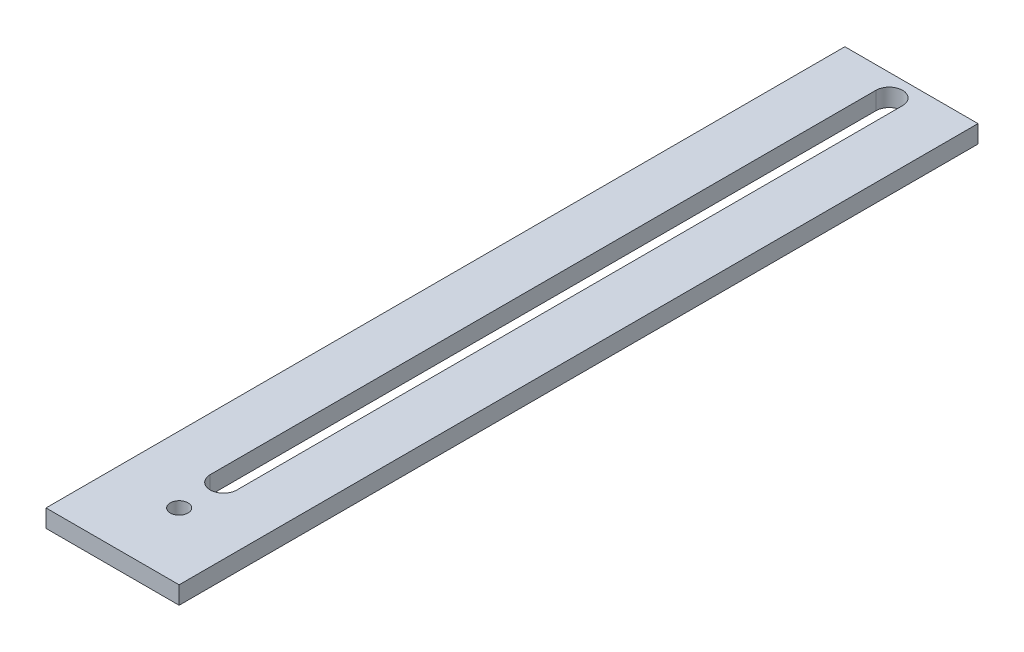
SolidWorks part; units mm, degrees
ref_plane "Front Plane" through (0, 0, 0) normal (0, 0, 1) x (1, 0, 0)
ref_plane "Top Plane" through (0, 0, 0) normal (0, 1, 0) x (1, 0, 0)
ref_plane "Right Plane" through (0, 0, 0) normal (1, 0, 0) x (0, 0, -1)
sketch "Sketch1" plane through (0, 0, 0) normal (0, 1, 0) x (1, 0, 0)
  line L1 (-15, 15) -> (15, 15)
  line L2 (-15, 15) -> (-15, -15)
  line L3 (-15, -15) -> (15, -15)
  line L4 (15, 15) -> (15, -15)
  line L5 (-15, 15) -> (15, -15) construction
  line L6 (-15, -15) -> (15, 15) construction
  circle A0 centre (0, 0) radius 2
  point P0 (0, 0)
  dimension "D1" = 4
  dimension "D2" = 30
  dimension "D3" = 30
extrude "Boss-Extrude1" add sketch "Sketch1" along normal blind 4
sketch "Sketch2" plane through (0, 0, -15) normal (0, 0, -1) x (-1, 0, 0)
  line L4 (-15, 0) -> (15, 0)
  line L5 (15, 0) -> (15, 4)
  line L6 (15, 4) -> (-15, 4)
  line L7 (-15, 4) -> (-15, 0)
  line L8 (-15, 0) -> (15, 0)
  line L9 (15, 0) -> (15, 4)
  line L10 (15, 4) -> (-15, 4)
  line L11 (-15, 4) -> (-15, 0)
  dimension "D1" = 0
extrude "Boss-Extrude2" add sketch "Sketch2" along normal blind 150
sketch "Sketch3" plane through (0, 4, 0) normal (0, 1, 0) x (1, 0, 0)
  line L0 (0, 10) -> (0, 160) construction
  line L1 (-3, 10) -> (-3, 160)
  line L2 (3, 10) -> (3, 160)
  arc A0 (-3, 10) -> (3, 10) centre (0, 10) ccw
  arc A1 (3, 160) -> (-3, 160) centre (0, 160) ccw
  point P3 (0, 85)
  point P8 (0, 0)
  dimension "D1" = 3
  dimension "D2" = 10
  dimension "D3" = 150
extrude "Cut-Extrude1" cut sketch "Sketch3" against normal through all
